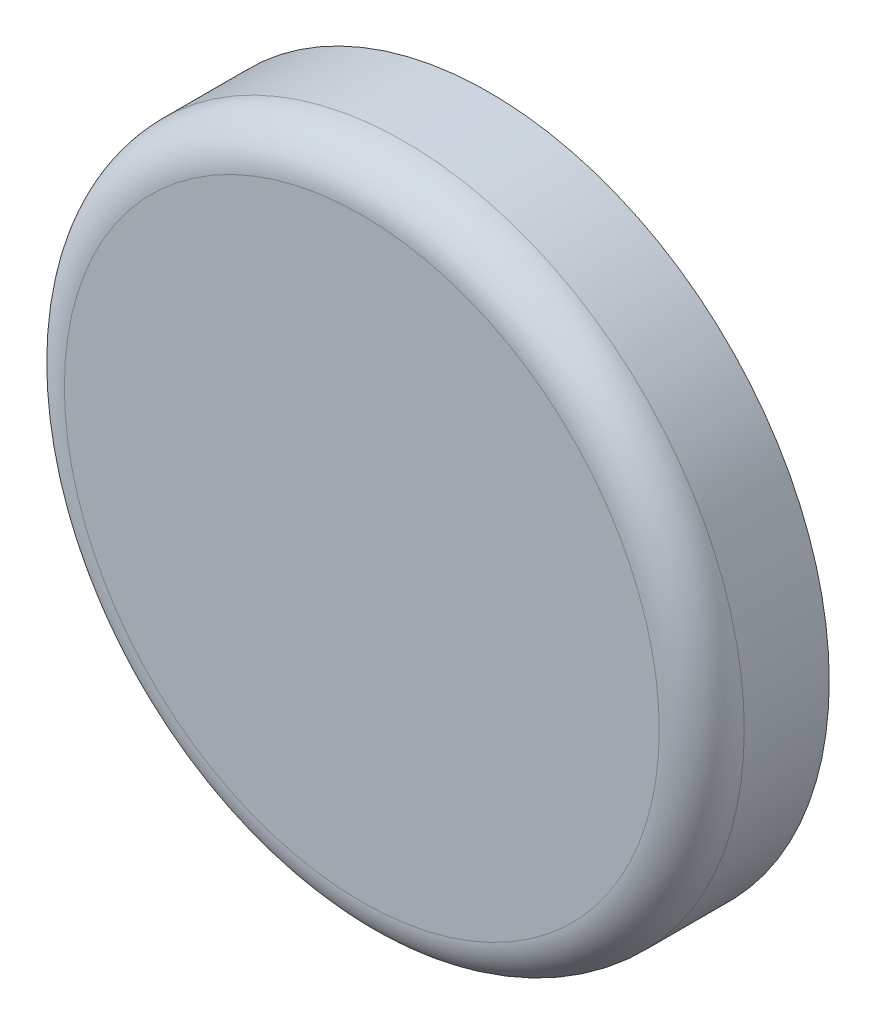
SolidWorks part; units mm, degrees
material "Silicon Dioxide"
ref_plane "Front Plane" through (0, 0, 0) normal (0, 0, 1) x (1, 0, 0)
ref_plane "Top Plane" through (0, 0, 0) normal (0, 1, 0) x (1, 0, 0)
ref_plane "Right Plane" through (0, 0, 0) normal (1, 0, 0) x (0, 0, -1)
sketch "Sketch1" plane through (0, 0, 0) normal (0, 0, 1) x (1, 0, 0)
  circle A0 centre (0, 0) radius 40
extrude "Boss-Extrude1" add sketch "Sketch1" along normal blind 15
fillet "Fillet1" radius 5 1 edges at (40, 0, 15)
scale "Scale1" scale about centroid uniform scaling yes scale factor 2
